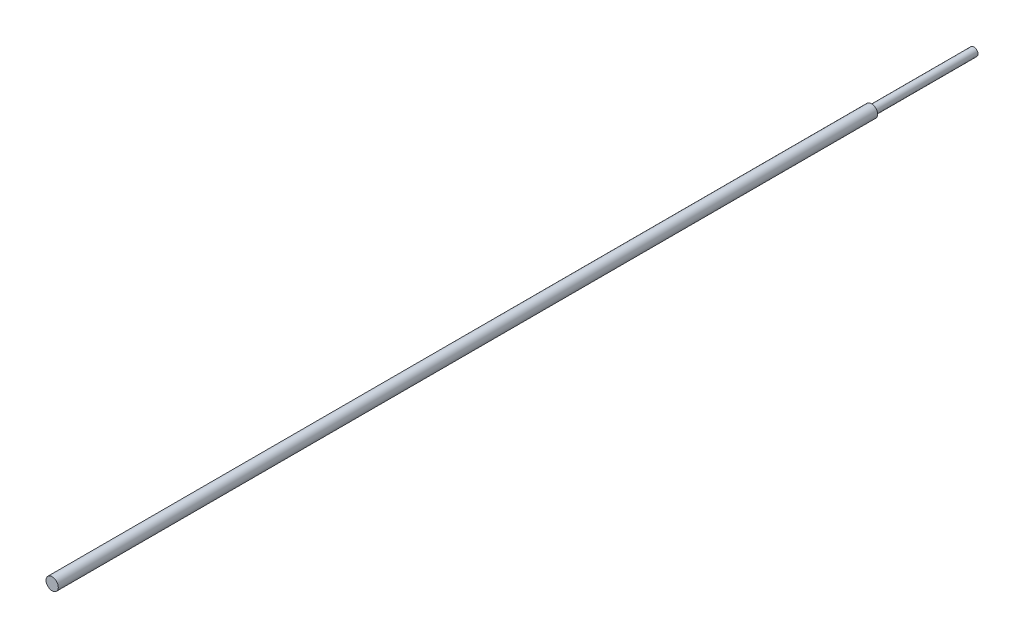
SolidWorks part; units mm, degrees
ref_plane "Спереди" through (0, 0, 0) normal (0, 0, 1) x (1, 0, 0)
ref_plane "Сверху" through (0, 0, 0) normal (0, 1, 0) x (1, 0, 0)
ref_plane "Справа" through (0, 0, 0) normal (1, 0, 0) x (0, 0, -1)
sketch "Эскиз1" plane through (0, 0, 0) normal (0, 0, 1) x (1, 0, 0)
  circle A0 centre (0, 0) radius 0.6
  dimension "D1" = 1.2
extrude "Вытянуть1" add sketch "Эскиз1" along normal blind 80
sketch "Эскиз2" plane through (0, 0, 0) normal (0, 0, -1) x (-1, 0, 0)
  circle A0 centre (0, 0) radius 0.4
  dimension "D1" = 0.8
extrude "Вытянуть2" add sketch "Эскиз2" along normal blind 10
